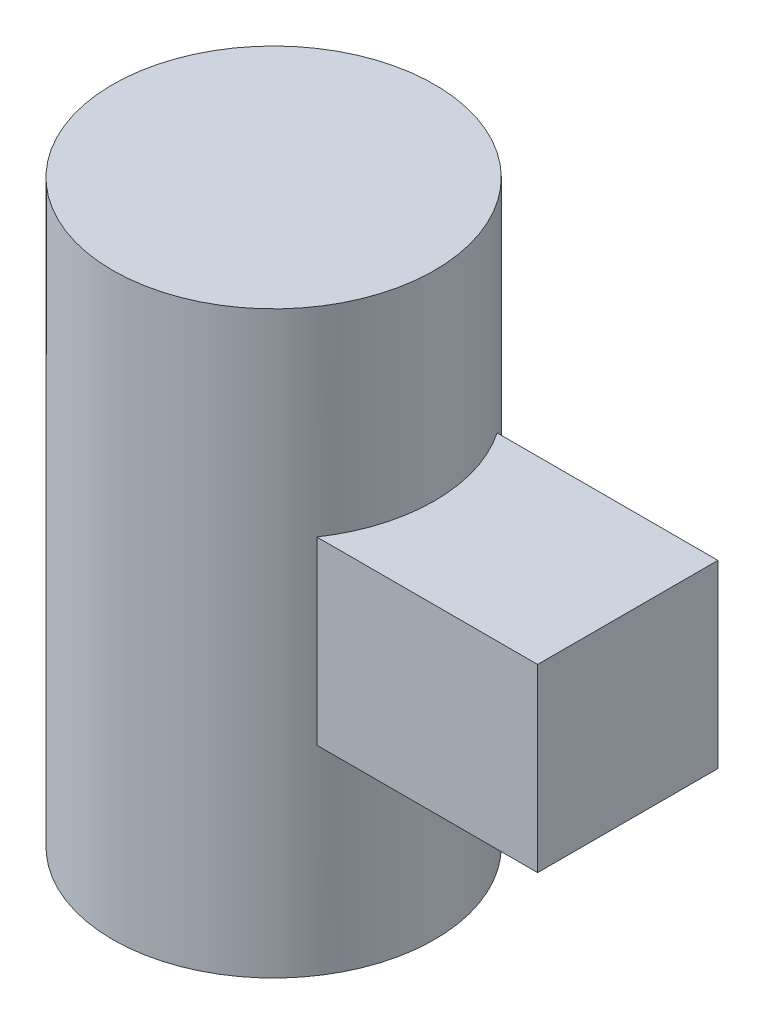
SolidWorks part; units mm, degrees
ref_plane "Front Plane" through (0, 0, 0) normal (0, 0, 1) x (1, 0, 0)
ref_plane "Top Plane" through (0, 0, 0) normal (0, 1, 0) x (1, 0, 0)
ref_plane "Right Plane" through (0, 0, 0) normal (1, 0, 0) x (0, 0, -1)
sketch "Sketch1" plane through (0, 0, 0) normal (0, 1, 0) x (1, 0, 0)
  circle A0 centre (0, 0) radius 31.75
  point P3 (0, 0)
  dimension "D1" = 63.5
extrude "Boss-Extrude1" add sketch "Sketch1" along normal mid plane 114.3
sketch "Sketch2" plane through (0, 0, 0) normal (1, 0, 0) x (0, 0, -1)
  line L1 (-17.78, -17.78) -> (17.78, -17.78)
  line L2 (-17.78, -17.78) -> (-17.78, 17.78)
  line L3 (-17.78, 17.78) -> (17.78, 17.78)
  line L4 (17.78, -17.78) -> (17.78, 17.78)
  line L5 (-17.78, -17.78) -> (17.78, 17.78) construction
  line L6 (-17.78, 17.78) -> (17.78, -17.78) construction
  point P0 (0, 0)
  dimension "D1" = 35.56
  dimension "D2" = 35.56
extrude "Boss-Extrude2" add sketch "Sketch2" along normal blind 69.85
